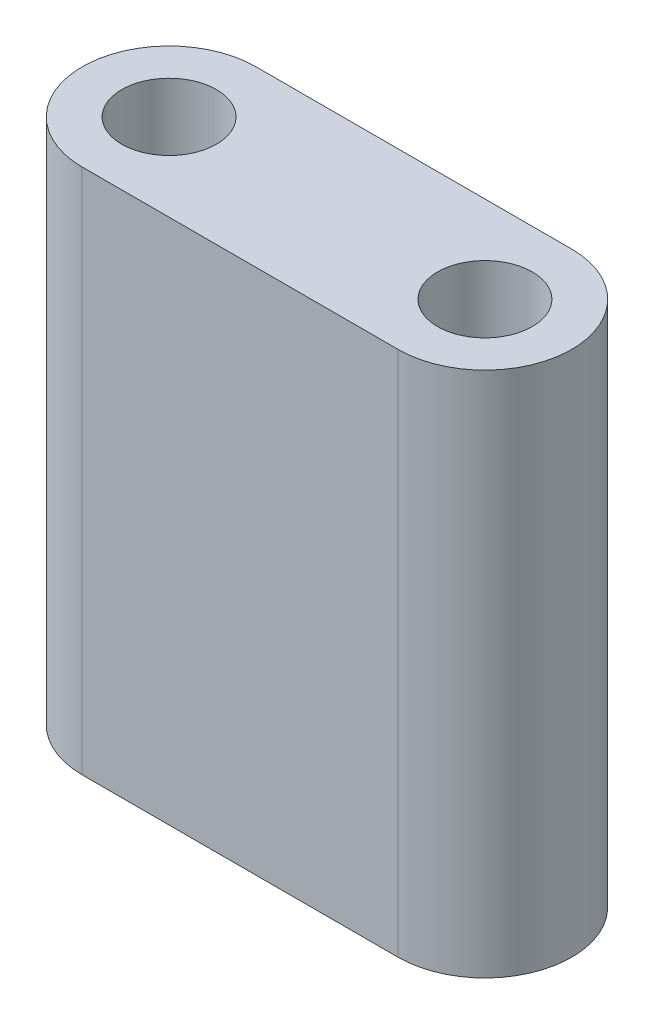
SolidWorks part; units mm, degrees
ref_plane "Front Plane" through (0, 0, 0) normal (0, 0, 1) x (1, 0, 0)
ref_plane "Top Plane" through (0, 0, 0) normal (0, 1, 0) x (1, 0, 0)
ref_plane "Right Plane" through (0, 0, 0) normal (1, 0, 0) x (0, 0, -1)
sketch "Sketch1" plane through (0, 0, 0) normal (0, 1, 0) x (1, 0, 0)
  line L0 (0, 0) -> (12, 0) construction
  line L1 (0, 3.3) -> (12, 3.3)
  line L2 (0, -3.3) -> (12, -3.3)
  line L3 (6, 3.3) -> (6, -3.3) construction
  arc A0 (0, 3.3) -> (0, -3.3) centre (0, 0) ccw
  arc A1 (12, -3.3) -> (12, 3.3) centre (12, 0) ccw
  circle A2 centre (0, 0) radius 1.8
  circle A3 centre (12, 0) radius 1.8
  point P3 (6, 0)
  dimension "D3" = 3.6
  dimension "D1" = 12
  dimension "D2" = 6.6
extrude "Boss-Extrude1" add sketch "Sketch1" along normal blind 20
